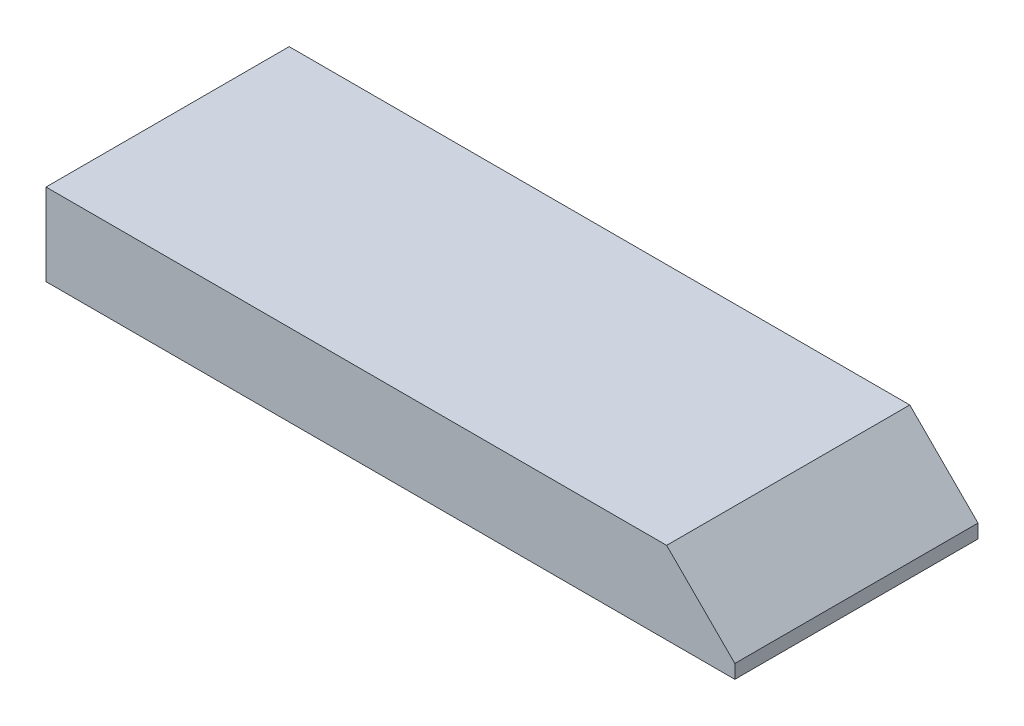
SolidWorks part; units mm, degrees
ref_plane "Front Plane" through (0, 0, 0) normal (0, 0, 1) x (1, 0, 0)
ref_plane "Top Plane" through (0, 0, 0) normal (0, 1, 0) x (1, 0, 0)
ref_plane "Right Plane" through (0, 0, 0) normal (1, 0, 0) x (0, 0, -1)
sketch "Sketch1" plane through (0, 0, 0) normal (0, 0, 1) x (1, 0, 0)
  line L0 (100, -9.8995) -> (90.1005, 0)
  line L1 (0, 0) -> (90.1005, 0)
  line L2 (0, 0) -> (0, -11.8995)
  line L3 (0, -11.8995) -> (100, -11.8995)
  line L4 (100, -9.8995) -> (100, -11.8995)
  point P5 (100, -9.8995)
  dimension "D1" = 14
  dimension "D2" = 100
  dimension "D3" = 2
  dimension "D4" = 45
extrude "Boss-Extrude1" add sketch "Sketch1" along normal blind 35.3
